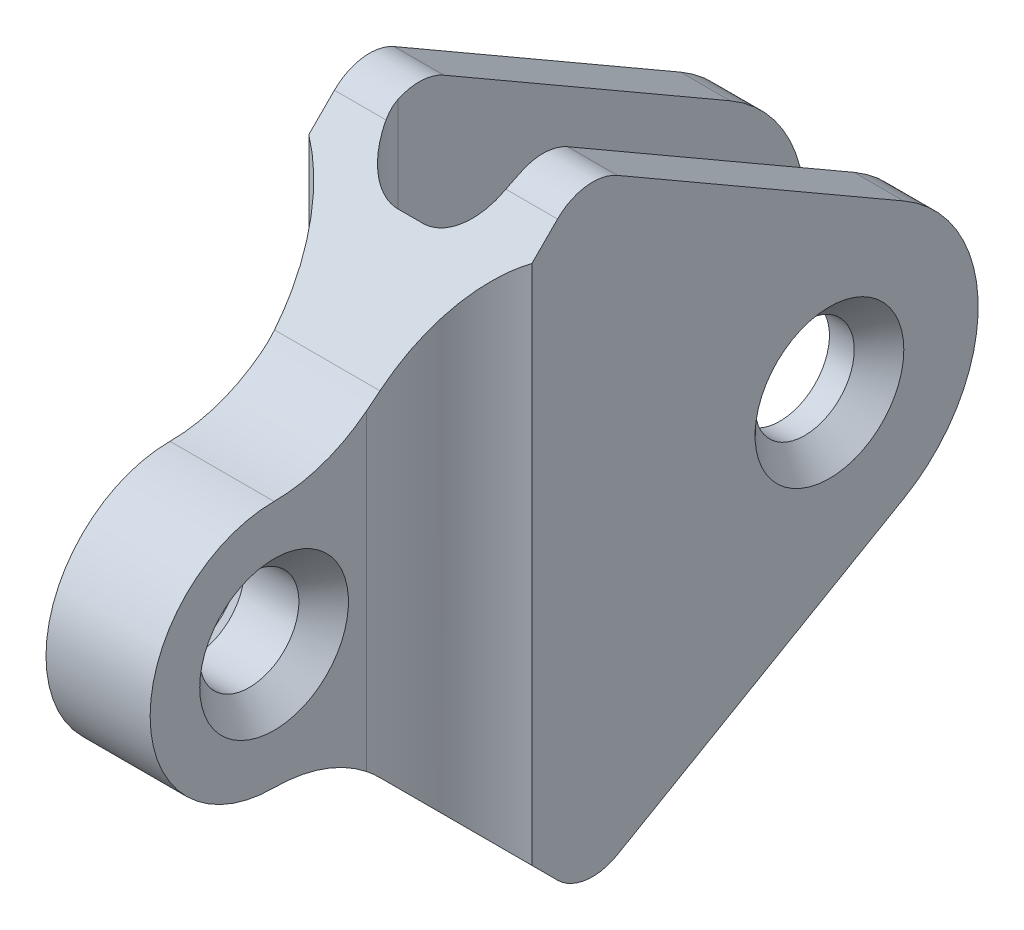
SolidWorks part; units mm, degrees
ref_plane "Front Plane" through (0, 0, 0) normal (1, 0, 0) x (0, 1, 0)
ref_plane "Top Plane" through (0, 0, 0) normal (0, 0, 1) x (0, 1, 0)
ref_plane "Right Plane" through (0, 0, 0) normal (0, 1, 0) x (-1, 0, 0)
sketch "Sketch1" plane through (0, 0, 0) normal (1, 0, 0) x (0, 1, 0)
  line L0 (25.9808, -15) -> (59.3297, 42.762)
  line L1 (57.7405, 54.8331) -> (33.7868, 78.7868)
  line L2 (0, 125) -> (0, -30) construction
  line L3 (-25.9808, -15) -> (-59.3297, 42.762)
  line L4 (-57.7405, 54.8331) -> (-33.7868, 78.7868)
  arc A0 (59.3297, 42.762) -> (57.7405, 54.8331) centre (50.6694, 47.762) ccw
  arc A1 (33.7868, 78.7868) -> (25, 100) centre (55, 100) cw
  arc A2 (25, 100) -> (-25, 100) centre (0, 100) ccw
  arc A3 (-25.9808, -15) -> (25.9808, -15) centre (0, 0) ccw
  circle A4 centre (0, 0) radius 10
  circle A5 centre (0, 100) radius 10
  arc A6 (-59.3297, 42.762) -> (-57.7405, 54.8331) centre (-50.6694, 47.762) cw
  arc A7 (-33.7868, 78.7868) -> (-25, 100) centre (-55, 100) ccw
  dimension "D2" = 25
  dimension "D3" = 10
  dimension "D4" = 20
  dimension "D5" = 20
  dimension "D6" = 30
  dimension "D1" = 100
  dimension "D7" = 60
extrude "Boss-Extrude1" add sketch "Sketch1" along normal mid plane 45
sketch "Sketch2" plane through (0, 0, 0) normal (0, 1, 0) x (-1, 0, 0)
  line L0 (-22.5, 125) -> (-10.5, 125)
  line L1 (22.5, 125) -> (-22.5, 125) construction
  line L2 (-22.5, 125) -> (-22.5, 100) construction
  line L3 (-10.5, 125) -> (-10.5, 81.3542)
  line L5 (-22.5, 60) -> (-22.5, 125)
  line L6 (0, 66.7364) -> (0, -66.7364) construction
  line L7 (22.5, 60) -> (22.5, 125)
  line L8 (10.5, 125) -> (10.5, 81.3542)
  line L9 (22.5, 125) -> (10.5, 125)
  line L10 (-12.5, -30) -> (-12.5, 52)
  line L11 (-22.5, -30) -> (22.5, -30) construction
  line L12 (-2.5, 62) -> (2.5, 62)
  line L13 (12.5, 52) -> (12.5, -30)
  line L14 (12.5, -30) -> (-12.5, -30)
  arc A0 (-10.5, 81.3542) -> (-22.5, 60) centre (-35.5, 81.3542) cw
  arc A1 (10.5, 81.3542) -> (22.5, 60) centre (35.5, 81.3542) ccw
  arc A2 (-12.5, 52) -> (-2.5, 62) centre (-2.5, 52) cw
  arc A3 (2.5, 62) -> (12.5, 52) centre (2.5, 52) cw
  point P28 (0, 62)
  dimension "D3" = 25
  dimension "D4" = 10
  dimension "D5" = 92
  dimension "D1" = 12
  dimension "D2" = 65
  dimension "D6" = 25
extrude "Cut-Extrude1" cut sketch "Sketch2" against normal through all both and the other way through all
chamfer "Chamfer1" distance 5 angle 45 4 edges at (10.5, 0, 110) (22.5, 0, -10) (-22.5, 0, -10) (-10.5, 0, 90)
